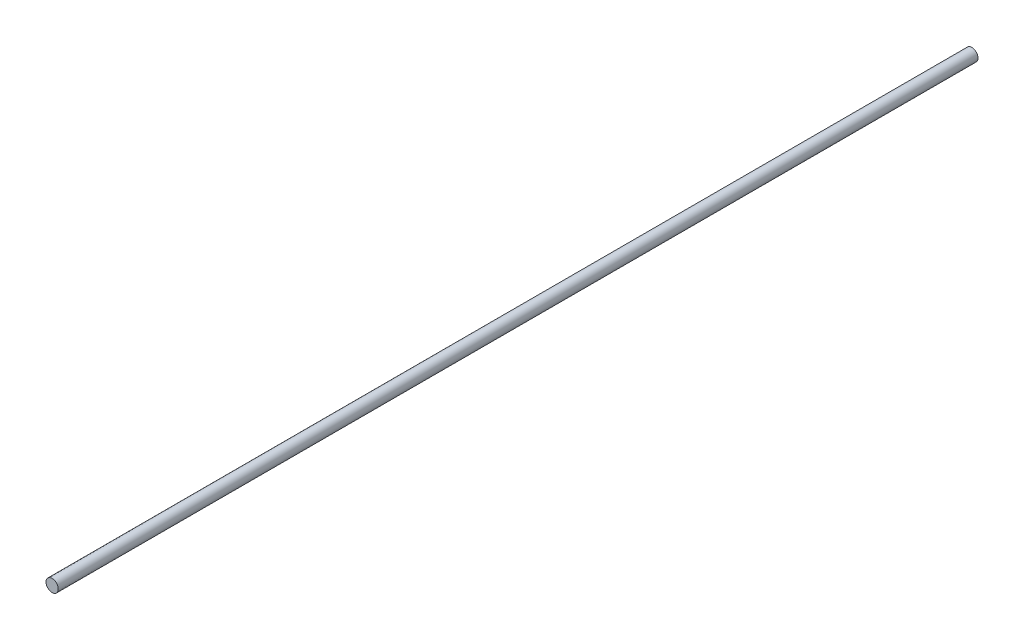
SolidWorks part; units mm, degrees
ref_plane "Plano frontal" through (0, 0, 0) normal (0, 0, 1) x (1, 0, 0)
ref_plane "Plano superior" through (0, 0, 0) normal (0, 1, 0) x (1, 0, 0)
ref_plane "Plano direito" through (0, 0, 0) normal (1, 0, 0) x (0, 0, -1)
sketch "Esboço1" plane through (0, 0, 0) normal (0, 0, 1) x (1, 0, 0)
  circle A0 centre (0, 0) radius 2
  dimension "D1" = 4
extrude "Ressalto-extrusão1" add sketch "Esboço1" along normal blind 300
